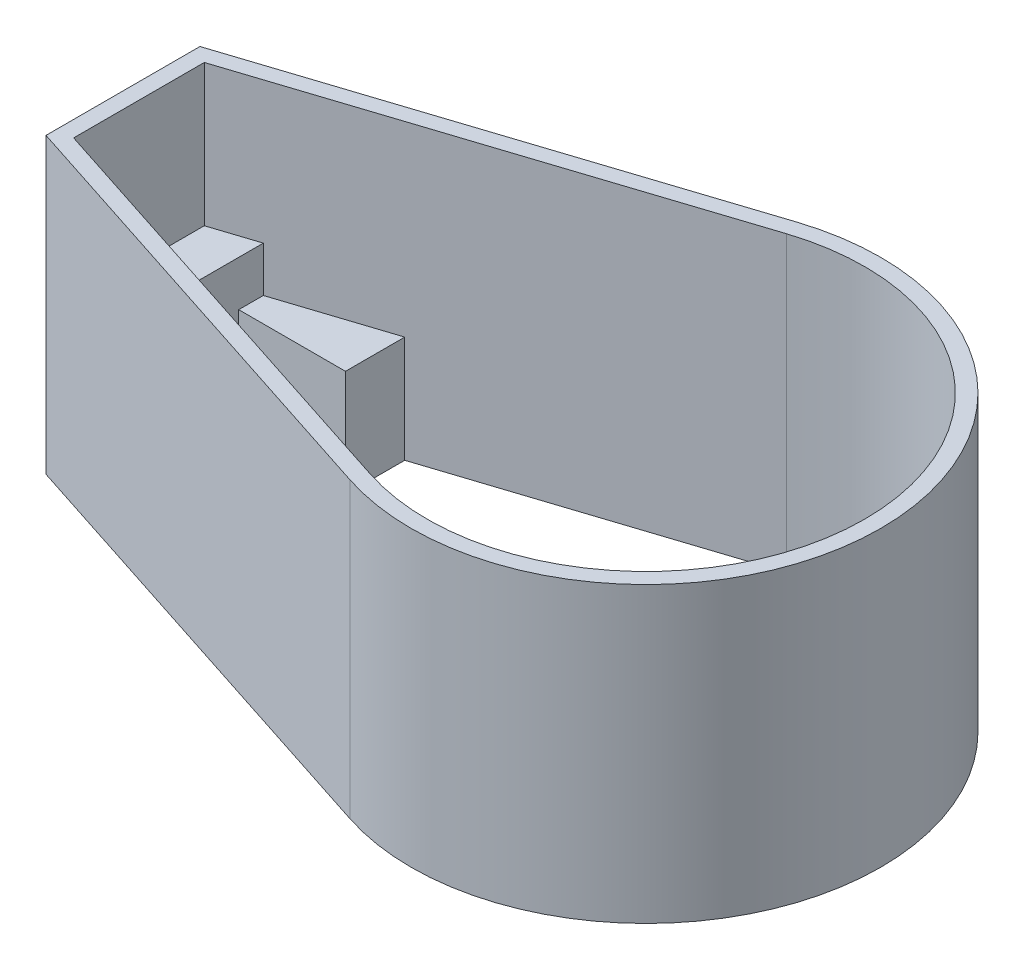
SolidWorks part; units mm, degrees
ref_plane "Plan de face" through (0, 0, 0) normal (0, 0, 1) x (1, 0, 0)
ref_plane "Plan de dessus" through (0, 0, 0) normal (0, 1, 0) x (1, 0, 0)
ref_plane "Plan de droite" through (0, 0, 0) normal (1, 0, 0) x (0, 0, -1)
sketch "Sketch1" plane through (0, 0, 0) normal (0, 1, 0) x (1, 0, 0)
  line L0 (-98, -14.4222) -> (-13.5967, -41.8465)
  line L1 (-13.5967, 41.8465) -> (-98, 14.4222)
  line L2 (-98, 14.4222) -> (-98, -14.4222)
  line L3 (-95, -12.2426) -> (-12.6697, -38.9933)
  line L4 (-12.6697, 38.9933) -> (-95, 12.2426)
  line L5 (-95, 12.2426) -> (-95, -12.2426)
  arc A0 (-13.5967, 41.8465) -> (-13.5967, -41.8465) centre (0, 0) cw
  arc A1 (-12.6697, 38.9933) -> (-12.6697, -38.9933) centre (0, 0) cw
  dimension "D2" = 44
  dimension "D1" = 28.8444
  dimension "D3" = 98
  dimension "D4" = 14.4222
  dimension "D5" = 3
extrude "Boss-Extrude1" add sketch "Sketch1" along normal blind 55 contours L1 L2 L0 A0 | L4 L5 L3 A1
sketch "Sketch2" plane through (0, 0, 0) normal (0, -1, 0) x (1, 0, 0)
  line L0 (-86.653, 14.9547) -> (-86.653, -14.9547)
  line L1 (-95, -12.2426) -> (-95, 12.2426) construction
  line L2 (-12.6697, -38.9933) -> (-95, -12.2426) construction
  line L3 (-95, 12.2426) -> (-12.6697, 38.9933) construction
  line L4 (-86.653, -14.9547) -> (-95, -12.2426)
  line L5 (-95, 12.2426) -> (-86.653, 14.9547)
  line L6 (-95, 12.2426) -> (-95, -12.2426)
  dimension "D1" = 8.347
extrude "Boss-Extrude2" add sketch "Sketch2" against normal blind 28.5
sketch "Sketch3" plane through (0, 0, 0) normal (0, -1, 0) x (1, 0, 0)
  line L0 (-86.653, 0) -> (-78.3875, 0) construction
  line L4 (-86.653, -10.35) -> (-66.653, -10.35)
  line L16 (-86.653, -14.9547) -> (-86.653, -10.35)
  line L17 (-66.653, 21.4531) -> (-86.653, 14.9547)
  line L18 (-66.653, 10.35) -> (-66.653, 21.4531)
  line L19 (-86.653, 14.9547) -> (-86.653, 10.35)
  line L20 (-86.653, 10.35) -> (-66.653, 10.35)
  line L21 (-66.653, -10.35) -> (-66.653, -21.4531)
  line L22 (-12.6697, -38.9933) -> (-86.653, -14.9547) construction
  line L23 (-66.653, -21.4531) -> (-86.653, -14.9547)
  line L24 (-86.653, -14.9547) -> (-86.653, 14.9547) construction
  point P8 (-66.653, -21.4531)
  point P9 (-86.653, -12.4021)
  point P10 (-78.3875, 0)
  dimension "D1" = 10.35
  dimension "D2" = 20
  dimension "D3" = 8.2655
extrude "Boss-Extrude3" add sketch "Sketch3" against normal blind 20
equation "\"D4@Sketch1\"=\"D1@Sketch1\"/2"
